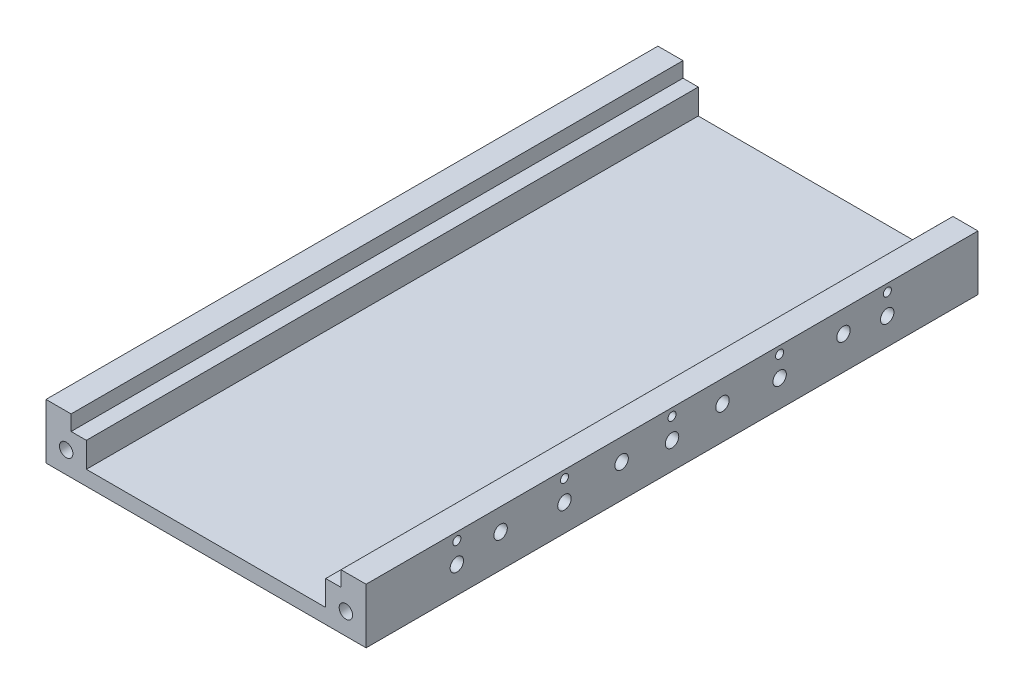
SolidWorks part; units mm, degrees
material "Aluminum"
ref_plane "Front Plane" through (0, 0, 0) normal (0, 0, 1) x (1, 0, 0)
ref_plane "Top Plane" through (0, 0, 0) normal (0, 1, 0) x (1, 0, 0)
ref_plane "Right Plane" through (0, 0, 0) normal (1, 0, 0) x (0, 0, -1)
sketch "Sketch1" plane through (0, 0, 0) normal (0, 0, 1) x (1, 0, 0)
  line L1 (44.5, 5.5) -> (-44.5, 5.5)
  line L6 (84.1457, 0) -> (-84.1457, 0) construction
  line L7 (-59.5, 0) -> (59.5, 0) construction
  line L9 (59.5, 0) -> (-59.5, 0)
  line L22 (50.17, 20.5) -> (59.5, 20.5)
  line L23 (50.17, 14.835) -> (50.17, 20.5)
  line L24 (44.5, 14.835) -> (50.17, 14.835)
  line L25 (44.5, 5.5) -> (44.5, 14.835)
  line L26 (-50.17, 20.5) -> (-59.5, 20.5)
  line L27 (-50.17, 14.835) -> (-50.17, 20.5)
  line L28 (-44.5, 14.835) -> (-50.17, 14.835)
  line L29 (-44.5, 5.5) -> (-44.5, 14.835)
  line L30 (-59.5, 20.5) -> (-59.5, 0)
  line L31 (59.5, 20.5) -> (59.5, 0)
  point P0 (0, 0)
  point P10 (0, 0)
  dimension "D1" = 119
  dimension "D2" = 89
  dimension "D3" = 100.34
  dimension "D4" = 9.33
  dimension "D5" = 20.5
extrude "Boss-Extrude1" add sketch "Sketch1" along normal blind 227.5
hole_wizard "Tap Drill for M5x0.8 Tap1" positions "Sketch4" profile "Sketch2" hole size "M5x0.8" standard "ANSI Metric"
sketch "Sketch4" plane through (0, 0, 227.5) normal (0, 0, 1) x (1, 0, 0)
  line L0 (0, 0) -> (0, 90.9259) construction
  line L3 (0, 0) -> (-119.5026, 0) construction
  point P4 (52, 8)
  point P6 (-52, 8)
  dimension "D1" = 8
  dimension "D2" = 8
  dimension "D4" = 52
  dimension "D5" = 52
sketch "Sketch2" plane through (52, 8, 227.5) normal (1, 0, 0) x (0, -1, 0)
  line L0 (0, 0) -> (0, 10)
  line L1 (0, 10) -> (2.5, 10)
  line L2 (2.5, 10) -> (2.5, 0)
  line L5 (2.5, 0) -> (0, 0)
  line L10 (0, 10) -> (-2.5, 10) construction
  line L11 (0, -6.35) -> (0, 107.95) construction
  dimension "Hole Dia." = 5
  dimension "Hole Depth" = 10
  dimension "Drill Angle" = 180
hole_wizard "Tap Drill for M5x0.8 Tap2" positions "Sketch6" profile "Sketch5" hole size "M5x0.8" standard "ANSI Metric"
sketch "Sketch6" plane through (0, 0, 0) normal (0, 0, -1) x (-1, 0, 0)
  point P0 (52, 8)
  point P3 (-52, 8)
sketch "Sketch5" plane through (-52, 8, 0) normal (1, 0, 0) x (0, 1, 0)
  line L0 (0, 0) -> (0, 10)
  line L1 (0, 10) -> (2.5, 10)
  line L2 (2.5, 10) -> (2.5, 0)
  line L5 (2.5, 0) -> (0, 0)
  line L10 (0, 10) -> (-2.5, 10) construction
  line L11 (0, -6.35) -> (0, 107.95) construction
  dimension "Hole Dia." = 5
  dimension "Hole Depth" = 10
  dimension "Drill Angle" = 180
hole_wizard "Tap Drill for M5x0.8 Tap3" positions "Sketch8" profile "Sketch7" hole size "M5x0.8" standard "ANSI Metric"
sketch "Sketch8" plane through (59.5, 0, 0) normal (1, 0, 0) x (0, 0, -1)
  line L2 (-113.75, 0) -> (-113.75, 73.5941) construction
  line L3 (-227.5, 0) -> (0, 0) construction
  point P0 (-193.75, 10)
  point P4 (-153.75, 10)
  point P6 (-113.75, 10)
  point P8 (-73.75, 10)
  point P10 (-33.75, 10)
  dimension "D1" = 40
  dimension "D2" = 40
  dimension "D3" = 40
  dimension "D4" = 40
  dimension "D5" = 10
  dimension "D6" = 10
  dimension "D7" = 10
sketch "Sketch7" plane through (59.5, 10, 193.75) normal (0, 1, 0) x (0, 0, -1)
  line L0 (0, 0) -> (0, 10)
  line L1 (0, 10) -> (2.5, 10)
  line L2 (2.5, 10) -> (2.5, 0)
  line L5 (2.5, 0) -> (0, 0)
  line L10 (0, 10) -> (-2.5, 10) construction
  line L11 (0, -6.35) -> (0, 107.95) construction
  dimension "Hole Dia." = 5
  dimension "Hole Depth" = 10
  dimension "Drill Angle" = 180
hole_wizard "Tap Drill for M5x0.8 Tap4" positions "Sketch10" profile "Sketch9" hole size "M5x0.8" standard "ANSI Metric"
sketch "Sketch10" plane through (-59.5, 0, 0) normal (-1, 0, 0) x (0, 0, 1)
  point P0 (193.75, 10)
  point P3 (153.75, 10)
  point P6 (113.75, 10)
  point P9 (73.75, 10)
  point P12 (33.75, 10)
sketch "Sketch9" plane through (-59.5, 10, 193.75) normal (0, 1, 0) x (0, 0, 1)
  line L0 (0, 0) -> (0, 10)
  line L1 (0, 10) -> (2.5, 10)
  line L2 (2.5, 10) -> (2.5, 0)
  line L5 (2.5, 0) -> (0, 0)
  line L10 (0, 10) -> (-2.5, 10) construction
  line L11 (0, -6.35) -> (0, 107.95) construction
  dimension "Hole Dia." = 5
  dimension "Hole Depth" = 10
  dimension "Drill Angle" = 180
hole_wizard "Tap Drill for M5x0.8 Tap5" positions "Sketch12" profile "Sketch13" hole size "M5x0.8" standard "ANSI Metric"
sketch "Sketch12" plane through (59.5, 0, 0) normal (1, 0, 0) x (0, 0, -1)
  point P0 (-177.5, 12.3462)
  point P3 (-132.5, 12.3462)
  point P6 (-95, 12.3462)
  point P9 (-50, 12.3462)
sketch "Sketch13" plane through (59.5, 12.3462, 177.5) normal (0, 1, 0) x (0, 0, -1)
  line L0 (0, 0) -> (0, 5.5)
  line L1 (0, 5.5) -> (2.5, 5.5)
  line L2 (2.5, 5.5) -> (2.5, 0)
  line L5 (2.5, 0) -> (0, 0)
  line L10 (0, 5.5) -> (-2.5, 5.5) construction
  line L11 (0, -6.35) -> (0, 107.95) construction
  dimension "Hole Dia." = 5
  dimension "Hole Depth" = 5.5
  dimension "Drill Angle" = 180
hole_wizard "Tap Drill for M5x0.8 Tap6" positions "Sketch15" profile "Sketch14" hole size "M5x0.8" standard "ANSI Metric"
sketch "Sketch15" plane through (-59.5, 0, 0) normal (-1, 0, 0) x (0, 0, 1)
  point P0 (50, 12.3462)
  point P3 (95, 12.3462)
  point P6 (132.5, 12.3462)
  point P9 (177.5, 12.3462)
sketch "Sketch14" plane through (-59.5, 12.3462, 50) normal (0, 1, 0) x (0, 0, 1)
  line L0 (0, 0) -> (0, 5.5)
  line L1 (0, 5.5) -> (2.5, 5.5)
  line L2 (2.5, 5.5) -> (2.5, 0)
  line L5 (2.5, 0) -> (0, 0)
  line L10 (0, 5.5) -> (-2.5, 5.5) construction
  line L11 (0, -6.35) -> (0, 107.95) construction
  dimension "Hole Dia." = 5
  dimension "Hole Depth" = 5.5
  dimension "Drill Angle" = 180
sketch "Sketch18" plane through (59.5, 0, 0) normal (1, 0, 0) x (0, 0, -1)
  circle A0 centre (-193.75, 17.6675) radius 1.5
  circle A1 centre (-153.75, 17.6675) radius 1.5
  circle A2 centre (-113.75, 17.6675) radius 1.5
  circle A3 centre (-73.75, 17.6675) radius 1.5
  circle A4 centre (-33.7042, 17.6675) radius 1.5
extrude "Cut-Extrude2" cut sketch "Sketch18" against normal blind 29
